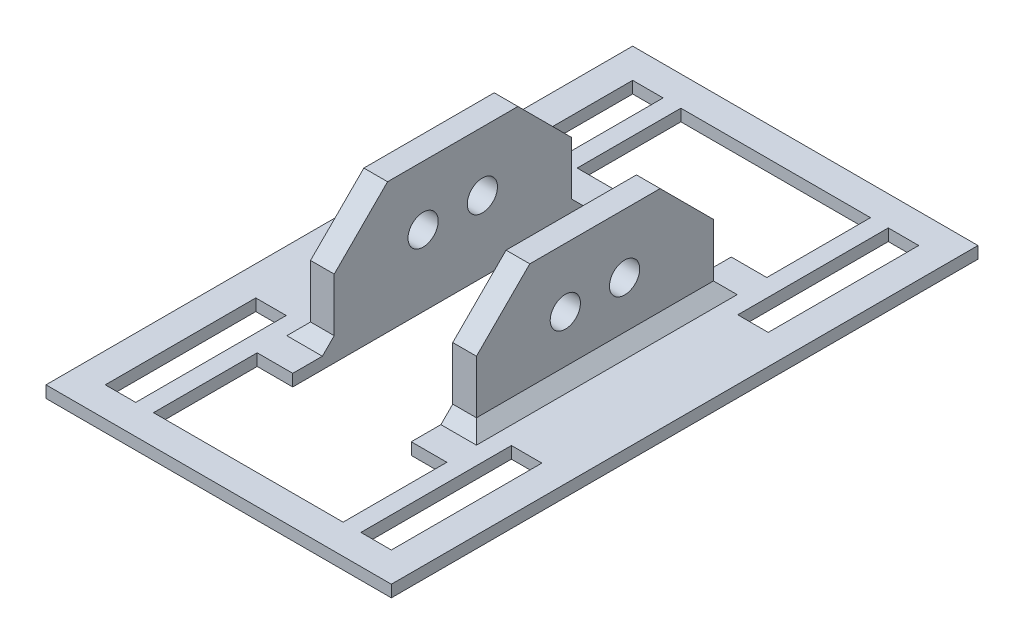
SolidWorks part; units mm, degrees
ref_plane "Front Plane" through (0, 0, 0) normal (0, 0, 1) x (1, 0, 0)
ref_plane "Top Plane" through (0, 0, 0) normal (0, 1, 0) x (1, 0, 0)
ref_plane "Right Plane" through (0, 0, 0) normal (1, 0, 0) x (0, 0, -1)
sketch "Sketch1" plane through (0, 0, 0) normal (0, 1, 0) x (1, 0, 0)
  line L0 (-5, 94) -> (-5, -5)
  line L1 (0, 89) -> (5.14, 89)
  line L2 (0, 89) -> (0, 63.6)
  line L3 (0, 63.6) -> (5.14, 63.6)
  line L4 (5.14, 89) -> (5.14, 63.6)
  line L5 (43.14, 89) -> (48.28, 89)
  line L6 (43.14, 89) -> (43.14, 63.6)
  line L7 (43.14, 63.6) -> (48.28, 63.6)
  line L8 (48.28, 89) -> (48.28, 63.6)
  line L9 (0, 25.4) -> (5.14, 25.4)
  line L10 (0, 25.4) -> (0, 0)
  line L11 (0, 0) -> (5.14, 0)
  line L12 (5.14, 25.4) -> (5.14, 0)
  line L13 (43.14, 25.4) -> (48.28, 25.4)
  line L14 (43.14, 25.4) -> (43.14, 0)
  line L15 (43.14, 0) -> (48.28, 0)
  line L16 (48.28, 25.4) -> (48.28, 0)
  line L21 (-5, -5) -> (53.28, -5)
  line L22 (53.28, 94) -> (53.28, -5)
  line L23 (-5, 94) -> (53.28, 94)
  dimension "D1" = 89
  dimension "D2" = 5.14
  dimension "D3" = 25.4
  dimension "D4" = 38
  dimension "D5" = 5
  dimension "D6" = 5
  dimension "D7" = 5
  dimension "D8" = 5
extrude "Boss-Extrude1" add sketch "Sketch1" along normal blind 2
sketch "Sketch2" plane through (0, 2, 0) normal (0, 1, 0) x (1, 0, 0)
  line L0 (24.14, 94) -> (24.14, -5) construction
  line L1 (53.28, 94) -> (-5, 94) construction
  line L2 (-5, -5) -> (53.28, -5) construction
  line L3 (-5, 44.5) -> (53.28, 44.5) construction
  line L4 (14.14, 64.5) -> (34.14, 64.5) construction
  line L5 (14.14, 64.5) -> (14.14, 24.5) construction
  line L6 (14.14, 24.5) -> (34.14, 24.5) construction
  line L7 (34.14, 64.5) -> (34.14, 24.5) construction
  line L8 (-5, 94) -> (-5, -5) construction
  line L9 (53.28, -5) -> (53.28, 94) construction
  line L11 (14.14, 64.5) -> (10.14, 64.5)
  line L12 (14.14, 64.5) -> (14.14, 24.5)
  line L13 (14.14, 24.5) -> (10.14, 24.5)
  line L14 (10.14, 64.5) -> (10.14, 24.5)
  line L15 (34.14, 64.5) -> (38.14, 64.5)
  line L16 (34.14, 64.5) -> (34.14, 24.5)
  line L17 (34.14, 24.5) -> (38.14, 24.5)
  line L18 (38.14, 64.5) -> (38.14, 24.5)
  dimension "D1" = 20
  dimension "D2" = 40
  dimension "D3" = 20
  dimension "D4" = 4
extrude "Boss-Extrude2" add sketch "Sketch2" along normal blind 20
sketch "Sketch3" plane through (38.14, 0, 0) normal (1, 0, 0) x (0, 0, -1)
  line L0 (24.5, 12) -> (64.5, 12) construction
  line L1 (24.5, 22) -> (24.5, 2) construction
  line L2 (64.5, 22) -> (64.5, 2) construction
  circle A0 centre (39.5, 12) radius 2.55
  circle A1 centre (49.5, 12) radius 2.55
  point P10 (35.9638, 14.952)
  point P11 (53.9847, 14.952)
  dimension "D1" = 5.1
  dimension "D2" = 10
  dimension "D3" = 15
extrude "Cut-Extrude1" cut sketch "Sketch3" against normal up to surface (28 mm away) up to face at (10.14, 12, -44.5)
chamfer "Chamfer1" distance 2 angle 45 6 edges at (12.14, 2, -64.5) (10.14, 2, -44.5) (12.14, 2, -24.5) (36.14, 2, -64.5) (36.14, 2, -24.5) (38.14, 2, -44.5)
sketch "Sketch4" plane through (10.14, 0, 0) normal (-1, 0, 0) x (0, 0, 1)
  line L0 (-55.5, 22) -> (-64.5, 13)
  line L1 (-64.5, 22) -> (-24.5, 22) construction
  line L2 (-64.5, 22) -> (-64.5, 4) construction
  line L3 (-64.5, 13) -> (-64.5, 22)
  line L4 (-64.5, 22) -> (-55.5, 22)
  line L5 (-33.5, 22) -> (-24.5, 13)
  line L6 (-24.5, 22) -> (-24.5, 4) construction
  line L7 (-24.5, 13) -> (-24.5, 22)
  line L8 (-24.5, 22) -> (-33.5, 22)
  point P12 (-24.5, 13)
  point P15 (-35.1367, 22)
  dimension "D1" = 45
extrude "Cut-Extrude2" cut sketch "Sketch4" against normal up to surface (28 mm away) up to face at (38.14, 12, -42.05)
sketch "Sketch5" plane through (0, 2, 0) normal (0, 1, 0) x (1, 0, 0)
  line L0 (8.14, 66.5) -> (14.14, 66.5) construction
  line L1 (34.14, 66.5) -> (40.14, 66.5) construction
  line L2 (40.14, 22.5) -> (34.14, 22.5) construction
  line L3 (14.14, 22.5) -> (8.14, 22.5) construction
  line L4 (34.14, 66.5) -> (34.14, 22.5) construction
  line L5 (14.14, 22.5) -> (14.14, 66.5) construction
  line L6 (8.14, 66.5) -> (14.14, 66.5)
  line L7 (34.14, 66.5) -> (40.14, 66.5)
  line L8 (40.14, 22.5) -> (34.14, 22.5)
  line L9 (14.14, 22.5) -> (8.14, 22.5)
  line L10 (34.14, 66.5) -> (34.14, 22.5)
  line L11 (14.14, 22.5) -> (14.14, 66.5)
  line L12 (5.14, 89) -> (0, 89) construction
  line L13 (8.14, 89) -> (40.14, 89)
  line L14 (14.14, 71.5) -> (14.14, 17.5)
  line L15 (8.14, 0) -> (40.14, 0)
  line L16 (34.14, 71.5) -> (34.14, 17.5)
  line L17 (0, 0) -> (5.14, 0) construction
  line L18 (40.14, 66.5) -> (40.14, 22.5) construction
  line L21 (14.14, 17.5) -> (8.14, 17.5)
  line L22 (8.14, 0) -> (8.14, 17.5)
  line L25 (34.14, 17.5) -> (40.14, 17.5)
  line L26 (40.14, 0) -> (40.14, 17.5)
  line L29 (14.14, 71.5) -> (8.14, 71.5)
  line L30 (8.14, 89) -> (8.14, 71.5)
  line L33 (34.14, 71.5) -> (40.14, 71.5)
  line L34 (40.14, 89) -> (40.14, 71.5)
  line L35 (8.14, 22.5) -> (8.14, 66.5) construction
  point P8 (0, 0)
  point P11 (0, 0)
  point P28 (18.5484, 0)
  point P29 (0, 0)
  point P30 (0, 0)
  point P31 (0, 0)
  point P32 (0, 0)
  point P33 (0, 0)
  point P34 (0, 0)
  point P37 (0, 0)
  line M24 (14.14, 66.5) -> (14.14, 22.5)
  line M48 (34.14, 22.5) -> (34.14, 66.5)
  dimension "D1" = 5
  dimension "D2" = 5
extrude "Cut-Extrude3" cut sketch "Sketch5" along direction (0, -1, 0) on the side against the normal up to surface (2 mm away) contours L34 L13 L30 L29 L14 L21 L22 L15 L26 L25 L16 L33 M24 M48
